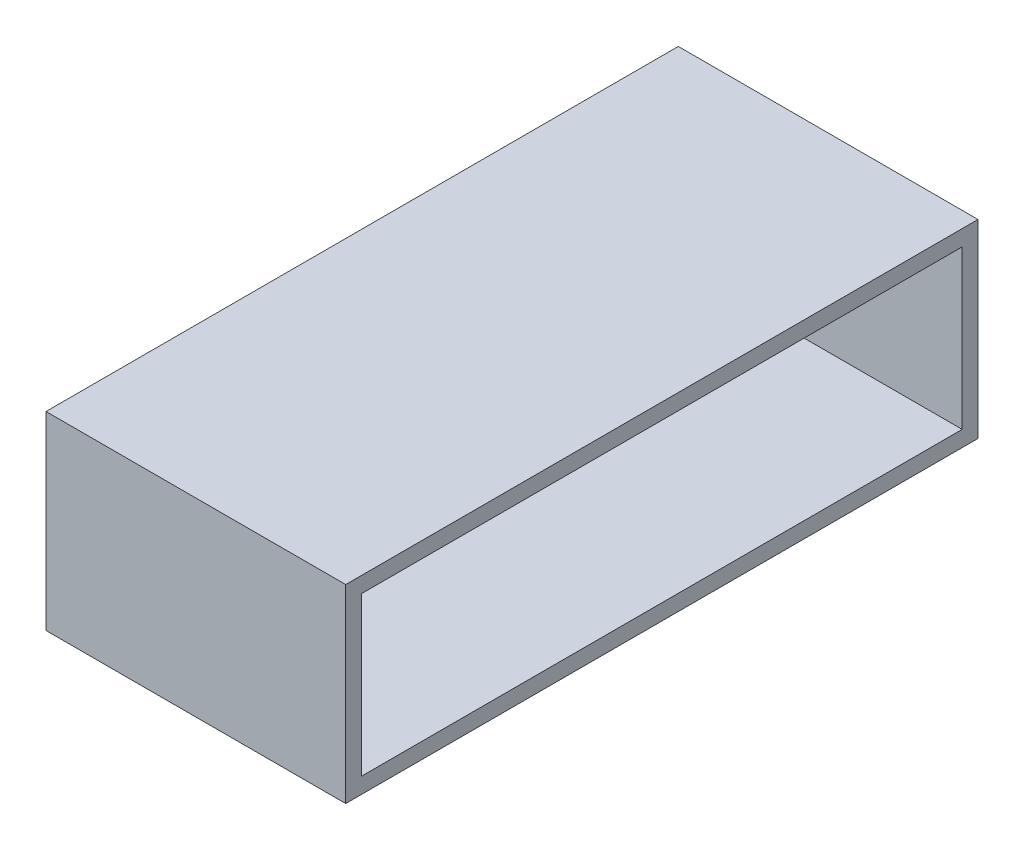
SolidWorks part; units mm, degrees
ref_plane "Front Plane" through (0, 0, 0) normal (0, 0, 1) x (1, 0, 0)
ref_plane "Top Plane" through (0, 0, 0) normal (0, 1, 0) x (1, 0, 0)
ref_plane "Right Plane" through (0, 0, 0) normal (1, 0, 0) x (0, 0, -1)
sketch "Sketch1" plane through (0, 0, 0) normal (0, 0, 1) x (1, 0, 0)
  line L1 (474, -300) -> (-474, -300)
  line L2 (474, -300) -> (474, 300)
  line L3 (474, 300) -> (-474, 300)
  line L4 (-474, -300) -> (-474, 300)
  line L5 (474, -300) -> (-474, 300) construction
  line L6 (474, 300) -> (-474, -300) construction
  point P0 (0, 0)
  dimension "D1" = 948
  dimension "D2" = 600
extrude "Boss-Extrude1" add sketch "Sketch1" along normal blind 2000
sketch "Sketch2" plane through (474, 0, 0) normal (1, 0, 0) x (0, 0, -1)
  line L0 (0, 0) -> (-2000, 0)
  line L1 (-2000, -300) -> (-2000, 300) construction
  line L2 (-1000, 300) -> (-1000, -300) construction
  line L3 (-2000, 300) -> (0, 300) construction
  line L4 (-2000, -300) -> (0, -300) construction
  line L6 (-50, -250) -> (-1950, -250)
  line L7 (-50, -250) -> (-50, 250)
  line L8 (-50, 250) -> (-1950, 250)
  line L9 (-1950, -250) -> (-1950, 250)
  line L10 (-50, -250) -> (-1950, 250) construction
  line L11 (-50, 250) -> (-1950, -250) construction
  point P11 (-1000, 0)
  dimension "D1" = 50
  dimension "D2" = 50
extrude "Cut-Extrude1" cut sketch "Sketch2" against normal through all contours L9 L0 L7 L8 | L9 L6 L7 L0
